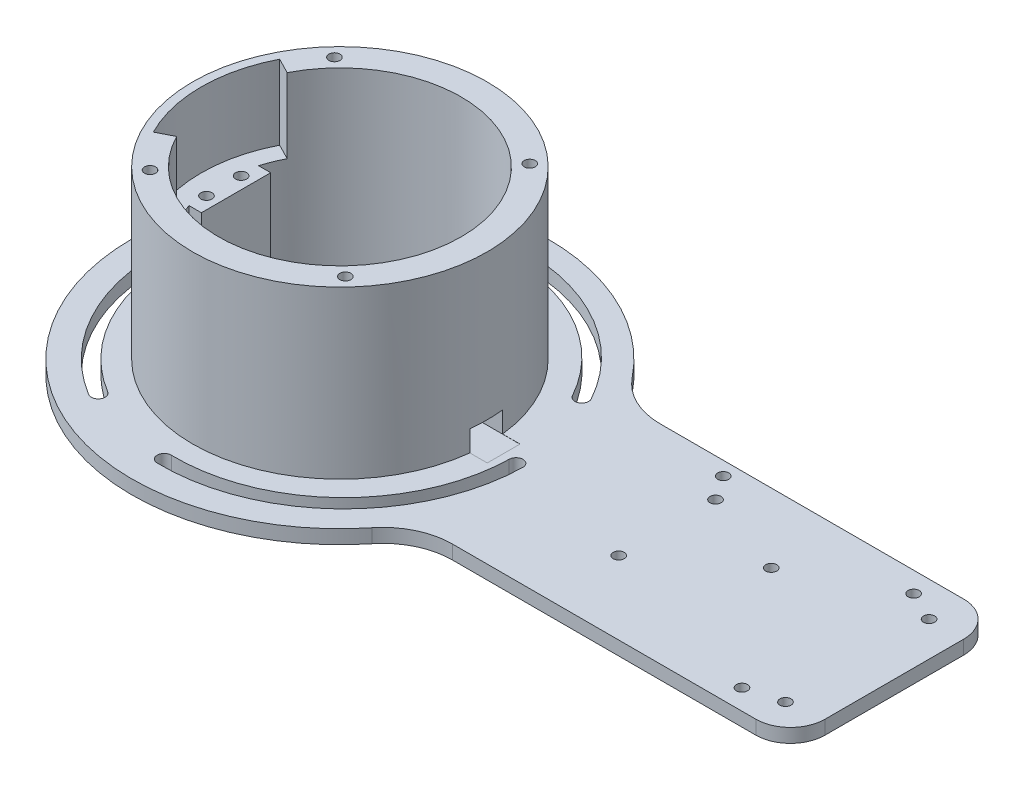
SolidWorks part; units mm, degrees
ref_plane "Ön Düzlem" through (0, 0, 0) normal (0, 0, 1) x (1, 0, 0)
ref_plane "Üst Düzlem" through (0, 0, 0) normal (0, 1, 0) x (1, 0, 0)
ref_plane "Sağ Düzlem" through (0, 0, 0) normal (1, 0, 0) x (0, 0, -1)
sketch "Sketch1" plane through (0, 0, 0) normal (0, 1, 0) x (1, 0, 0)
  line L0 (0, 0) -> (160, 0) construction
  line L1 (62.45, -30) -> (150, -30)
  line L2 (62.45, 30) -> (150, 30)
  line L4 (160, -20) -> (160, 20)
  arc A0 (46.8375, 37.5) -> (46.8375, -37.5) centre (0, 0) ccw
  circle A1 centre (0, 0) radius 35
  arc A2 (46.8375, -37.5) -> (62.45, -30) centre (62.45, -50) cw
  arc A3 (46.8375, 37.5) -> (62.45, 30) centre (62.45, 50) ccw
  arc A4 (150, -30) -> (160, -20) centre (150, -20) ccw
  arc A5 (150, 30) -> (160, 20) centre (150, 20) cw
  dimension "D1" = 20
  dimension "D2" = 120
  dimension "D3" = 70
  dimension "D4" = 10
extrude "Boss-Extrude1" add sketch "Sketch1" along normal blind 4
sketch "Sketch2" plane through (0, 4, 0) normal (0, 1, 0) x (1, 0, 0)
  circle A0 centre (0, 0) radius 35
  circle A1 centre (0, 0) radius 42.5
extrude "Boss-Extrude2" add sketch "Sketch2" along normal blind 48
sketch "Sketch3" plane through (0, 4, 0) normal (0, 1, 0) x (1, 0, 0)
  circle A0 centre (150, 20) radius 1.6
  circle A1 centre (150, -21.4336) radius 1.6
  arc A2 (-26.3011, -43.4279) -> (-43.4279, 26.3011) centre (0, 0) cw construction
  arc A7 (-45.1386, 27.3372) -> (-27.3372, -45.1386) centre (0, 0) ccw
  arc A8 (-41.7172, 25.2651) -> (-25.2651, -41.7172) centre (0, 0) ccw
  arc A9 (-41.7172, 25.2651) -> (-45.1386, 27.3372) centre (-43.4279, 26.3011) ccw
  arc A10 (-27.3372, -45.1386) -> (-25.2651, -41.7172) centre (-26.3011, -43.4279) ccw
  arc A11 (-24.4417, 45.3202) -> (44.5088, 25.2879) centre (0.0174, 0.8288) cw construction
  arc A12 (46.2614, 26.2514) -> (-25.4052, 47.0728) centre (0.0174, 0.8288) ccw
  arc A13 (42.7561, 24.3244) -> (-23.4782, 43.5676) centre (0.0174, 0.8288) ccw
  arc A14 (42.7561, 24.3244) -> (46.2614, 26.2514) centre (44.5088, 25.2879) ccw
  arc A15 (-25.4052, 47.0728) -> (-23.4782, 43.5676) centre (-24.4417, 45.3202) ccw
  arc A16 (51.4867, -0.6641) -> (-0.337, -50.3608) centre (0.7265, 0.3994) cw construction
  arc A17 (-0.3789, -52.3604) -> (53.4863, -0.706) centre (0.7265, 0.3994) ccw
  arc A18 (-0.2951, -48.3613) -> (49.4871, -0.6222) centre (0.7265, 0.3994) ccw
  arc A19 (-0.2951, -48.3613) -> (-0.3789, -52.3604) centre (-0.337, -50.3608) ccw
  arc A20 (53.4863, -0.706) -> (49.4871, -0.6222) centre (51.4867, -0.6641) ccw
  point P9 (-49.3059, -12.1105)
  point P20 (14.1823, 49.5842)
  point P28 (35.8674, -36.2455)
  dimension "D1" = 3
extrude "Cut-Extrude1" cut sketch "Sketch3" against normal blind 48
sketch "Sketch4" plane through (0, 4, 0) normal (0, 1, 0) x (1, 0, 0)
  circle A0 centre (89.34, -8.89) radius 1.6
  circle A1 centre (89.34, 19.05) radius 1.6
  circle A2 centre (140.14, -24.13) radius 1.6
  circle A3 centre (141.41, 24.13) radius 1.6
extrude "Cut-Extrude2" cut sketch "Sketch4" against normal blind 10
sketch "Sketch8" plane through (0, 52, 0) normal (0, 1, 0) x (1, 0, 0)
  circle A0 centre (-26.597, -28.1809) radius 1.6
  circle A2 centre (-28.1809, 26.597) radius 1.6
  circle A3 centre (26.597, 28.1809) radius 1.6
  circle A4 centre (28.1809, -26.597) radius 1.6
  dimension "D1" = 38.75
  dimension "D2" = 4
extrude "Cut-Extrude6" cut sketch "Sketch8" against normal blind 15
sketch "Sketch10" plane through (0, 4, 0) normal (0, 1, 0) x (1, 0, 0)
  circle A0 centre (84.581, 26.035) radius 1.6
  circle A1 centre (114.426, 10.033) radius 1.6
extrude "Cut-Extrude8" cut sketch "Sketch10" against normal blind 10
sketch "Sketch12" plane through (0, 0, 0) normal (0, -1, 0) x (1, 0, 0)
  line L0 (-29.4, -1.5505) -> (-29.4, 1.7015) construction
  line L5 (-30.025, -10.0609) -> (-30.025, 9.9391)
  line L6 (-30.025, -10.0609) -> (-33.5228, -10.0609)
  line L8 (-33.5591, 9.9391) -> (-30.025, 9.9391)
  line L9 (-28.4504, -10) -> (-32.5557, -10.0609) construction
  line L10 (-31.7485, 9.9391) -> (-26.6515, 10) construction
  line L11 (11, -3.5637) -> (11, 4.3261) construction
  line L16 (12.25, -10) -> (12.25, 10)
  line L17 (12.25, -10) -> (33.541, -10)
  line L21 (12.25, 10) -> (33.541, 10)
  circle A0 centre (0, 0) radius 35 construction
  arc A1 (33.541, -10) -> (33.541, 10) centre (0, 0) ccw
  arc A2 (-33.5591, 9.9391) -> (-33.5228, -10.0609) centre (0, 0) ccw
  dimension "D1" = 1.25
  dimension "D3" = 1.25
extrude "Boss-Extrude3" add sketch "Sketch12" against normal blind 30.5
chamfer "Chamfer1" distance 20 angle 45 1 edges at (12.25, 0, 0)
sketch "Sketch14" plane through (0, 52, 0) normal (0, 1, 0) x (1, 0, 0)
  line L0 (0, 0) -> (-35.6061, -18.2264)
  line L1 (-16.9676, 0) -> (-50.3088, 0) construction
  line L2 (0, 0) -> (-35.6061, 18.2264)
  arc A0 (-35.6061, 18.2264) -> (-35.6061, -18.2264) centre (0, 0) ccw
extrude "Cut-Extrude11" cut sketch "Sketch14" against normal up to surface (21.5 mm away) up to face at (23.2603, 30.5, 0)
sketch "Sketch15" plane through (0, 52, 0) normal (0, 1, 0) x (1, 0, 0)
  circle A0 centre (-33.5, -5) radius 1.6
  circle A1 centre (-33.5, 5) radius 1.6
  circle A2 centre (15.1, -5) radius 1.6
  circle A3 centre (15.1, 5) radius 1.6
extrude "Cut-Extrude13" cut sketch "Sketch15" against normal blind 46
sketch "Sketch16" plane through (12.25, 0, 0) normal (-1, 0, 0) x (0, 0, 1)
  line L5 (-4.7276, 3.9584) -> (4.7276, 3.9584)
  line L6 (-4.7276, 3.9584) -> (-4.7276, 10.0416)
  line L7 (-4.7276, 10.0416) -> (4.7276, 10.0416)
  line L8 (4.7276, 3.9584) -> (4.7276, 10.0416)
  line L9 (-4.7276, 3.9584) -> (4.7276, 10.0416) construction
  line L10 (-4.7276, 10.0416) -> (4.7276, 3.9584) construction
  point P0 (-0.1272, 7.5745)
  point P1 (0, 7)
extrude "Cut-Extrude15" cut sketch "Sketch16" against normal blind 35
